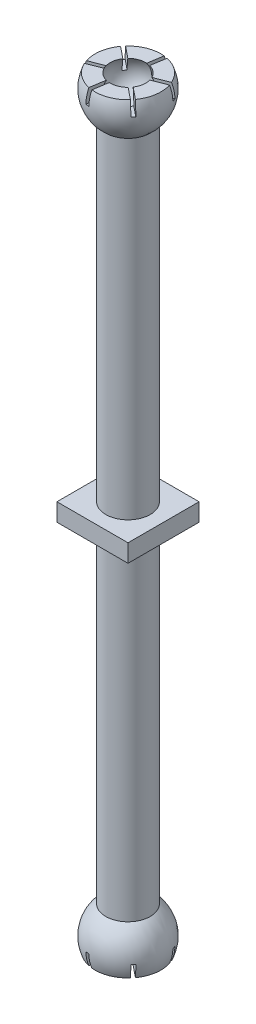
SolidWorks part; units mm, degrees
ref_plane "Front Plane" through (0, 0, 0) normal (0, 0, 1) x (1, 0, 0)
ref_plane "Top Plane" through (0, 0, 0) normal (0, 1, 0) x (1, 0, 0)
ref_plane "Right Plane" through (0, 0, 0) normal (1, 0, 0) x (0, 0, -1)
sketch "Sketch1" plane through (0, 0, 0) normal (0, 1, 0) x (1, 0, 0)
  circle A0 centre (0, 0) radius 25
  dimension "D1" = 50
extrude "Boss-Extrude1" add sketch "Sketch1" along normal mid plane 826
ref_plane "Plane1" through (0, -413, 0) normal (0, -1, 0) x (-1, 0, 0)
ref_plane "Plane2" through (0, 413, 0) normal (0, 1, 0) x (1, 0, 0)
sketch "Sketch2" plane through (0, -413, 0) normal (0, -1, 0) x (1, 0, 0)
  line L0 (0, 40) -> (0, -40)
  arc A0 (0, 40) -> (0, -40) centre (0, 0) ccw
  dimension "D1" = 40
revolve "Revolve1" add sketch "Sketch2" angle 360 about L0
sketch "Sketch3" plane through (0, 413, 0) normal (0, 1, 0) x (1, 0, 0)
  line L0 (0, 40) -> (0, -40)
  arc A0 (0, 40) -> (0, -40) centre (0, 0) ccw
  dimension "D1" = 40
revolve "Revolve2" add sketch "Sketch3" angle 360 about L0
ref_plane "Plane3" through (0, 428, 0) normal (0, 1, 0) x (1, 0, 0)
ref_plane "Plane4" through (0, -428, 0) normal (0, -1, 0) x (-1, 0, 0)
sketch "Sketch4" plane through (0, 428, 0) normal (0, 1, 0) x (1, 0, 0)
  circle A0 centre (0, 0) radius 49.2947
extrude "Cut-Extrude1" cut sketch "Sketch4" along normal through all contours A0
sketch "Sketch5" plane through (0, -428, 0) normal (0, -1, 0) x (-1, 0, 0)
  circle A0 centre (0, 0) radius 48.0807
extrude "Cut-Extrude2" cut sketch "Sketch5" along normal through all
sketch "Sketch6" plane through (0, -413, 0) normal (0, -1, 0) x (-1, 0, 0)
  line L0 (13.1663, 21.2521) -> (-13.1663, -21.2521)
  arc A0 (-13.1663, -21.2521) -> (13.1663, 21.2521) centre (0, 0) cw
  dimension "D1" = 25
revolve "Cut-Revolve1" cut sketch "Sketch6" angle 360 about L0
sketch "Sketch7" plane through (0, -413, 0) normal (0, -1, 0) x (-1, 0, 0)
  line L0 (-3.9517, -0.62) -> (-40.8587, 13.6085)
  line L1 (-1.4389, -3.7322) -> (4.6924, -42.8089)
  line L4 (-1.4389, -3.7322) -> (-32.2146, -28.5804)
  line L6 (1.4389, 3.7322) -> (-4.6924, 42.8089)
  line L7 (3.9517, 0.62) -> (34.7274, 25.4682)
  line L8 (2.5128, -3.1122) -> (39.4198, -17.3407)
  line L12 (-2.5128, 3.1122) -> (-8.644, 42.1889)
  line L36 (-3.9517, -0.62) -> (-34.7274, -25.4682)
  line L37 (2.5128, -3.1122) -> (8.644, -42.1889)
  line L38 (3.9517, 0.62) -> (40.8587, -13.6085)
  line L39 (1.4389, 3.7322) -> (32.2146, 28.5804)
  line L40 (-2.5128, 3.1122) -> (-39.4198, 17.3407)
  arc A0 (-39.4198, 17.3407) -> (-40.8587, 13.6085) centre (0, 0) ccw
  arc A1 (-34.7274, -25.4682) -> (-32.2146, -28.5804) centre (0, 0) ccw
  arc A2 (4.6924, -42.8089) -> (8.644, -42.1889) centre (0, 0) ccw
  arc A3 (39.4198, -17.3407) -> (40.8587, -13.6085) centre (0, 0) ccw
  arc A4 (34.7274, 25.4682) -> (32.2146, 28.5804) centre (0, 0) ccw
  arc A5 (-4.6924, 42.8089) -> (-8.644, 42.1889) centre (0, 0) ccw
  point P11 (0, 0)
extrude "Cut-Extrude3" cut sketch "Sketch7" along normal through all
sketch "Sketch8" plane through (0, 413, 0) normal (0, 1, 0) x (1, 0, 0)
  line L0 (15.0325, 19.9756) -> (-15.0325, -19.9756)
  arc A0 (15.0325, 19.9756) -> (-15.0325, -19.9756) centre (0, 0) ccw
  dimension "D1" = 25
revolve "Cut-Revolve2" cut sketch "Sketch8" angle 360 about L0
sketch "Sketch9" plane through (0, 413, 0) normal (0, 1, 0) x (1, 0, 0)
  line L12 (3.9517, -0.62) -> (40.8587, 13.6085)
  line L13 (39.4198, 17.3407) -> (2.5128, 3.1122)
  line L14 (2.5128, 3.1122) -> (8.644, 42.1889)
  line L15 (4.6924, 42.8089) -> (-1.4389, 3.7322)
  line L16 (-1.4389, 3.7322) -> (-32.2146, 28.5804)
  line L17 (-34.7274, 25.4682) -> (-3.9517, 0.62)
  line L18 (-3.9517, 0.62) -> (-40.8587, -13.6085)
  line L19 (-39.4198, -17.3407) -> (-2.5128, -3.1122)
  line L20 (-2.5128, -3.1122) -> (-8.644, -42.1889)
  line L21 (-4.6924, -42.8089) -> (1.4389, -3.7322)
  line L22 (1.4389, -3.7322) -> (32.2146, -28.5804)
  line L23 (34.7274, -25.4682) -> (3.9517, -0.62)
  line L24 (3.9517, -0.62) -> (40.8587, 13.6085)
  line L25 (39.4198, 17.3407) -> (2.5128, 3.1122)
  line L26 (2.5128, 3.1122) -> (8.644, 42.1889)
  line L27 (4.6924, 42.8089) -> (-1.4389, 3.7322)
  line L28 (-1.4389, 3.7322) -> (-32.2146, 28.5804)
  line L29 (-34.7274, 25.4682) -> (-3.9517, 0.62)
  line L30 (-3.9517, 0.62) -> (-40.8587, -13.6085)
  line L31 (-39.4198, -17.3407) -> (-2.5128, -3.1122)
  line L32 (-2.5128, -3.1122) -> (-8.644, -42.1889)
  line L33 (-4.6924, -42.8089) -> (1.4389, -3.7322)
  line L34 (1.4389, -3.7322) -> (32.2146, -28.5804)
  line L35 (34.7274, -25.4682) -> (3.9517, -0.62)
  arc A6 (40.8587, 13.6085) -> (39.4198, 17.3407) centre (0, 0) ccw
  arc A7 (8.644, 42.1889) -> (4.6924, 42.8089) centre (0, 0) ccw
  arc A8 (-32.2146, 28.5804) -> (-34.7274, 25.4682) centre (0, 0) ccw
  arc A9 (-40.8587, -13.6085) -> (-39.4198, -17.3407) centre (0, 0) ccw
  arc A10 (-8.644, -42.1889) -> (-4.6924, -42.8089) centre (0, 0) ccw
  arc A11 (32.2146, -28.5804) -> (34.7274, -25.4682) centre (0, 0) ccw
  arc A12 (40.8587, 13.6085) -> (39.4198, 17.3407) centre (0, 0) ccw
  arc A13 (8.644, 42.1889) -> (4.6924, 42.8089) centre (0, 0) ccw
  arc A14 (-32.2146, 28.5804) -> (-34.7274, 25.4682) centre (0, 0) ccw
  arc A15 (-40.8587, -13.6085) -> (-39.4198, -17.3407) centre (0, 0) ccw
  arc A16 (-8.644, -42.1889) -> (-4.6924, -42.8089) centre (0, 0) ccw
  arc A17 (32.2146, -28.5804) -> (34.7274, -25.4682) centre (0, 0) ccw
  dimension "D1" = 0
extrude "Cut-Extrude4" cut sketch "Sketch9" along normal through all
sketch "Sketch10" plane through (0, 0, 0) normal (0, 1, 0) x (1, 0, 0)
  line L1 (-40, 40) -> (40, 40)
  line L2 (-40, 40) -> (-40, -40)
  line L3 (-40, -40) -> (40, -40)
  line L4 (40, 40) -> (40, -40)
  line L5 (-40, 40) -> (40, -40) construction
  line L6 (-40, -40) -> (40, 40) construction
  point P0 (0, 0)
  dimension "D1" = 80
  dimension "D2" = 80
extrude "Boss-Extrude2" add sketch "Sketch10" along normal mid plane 20
